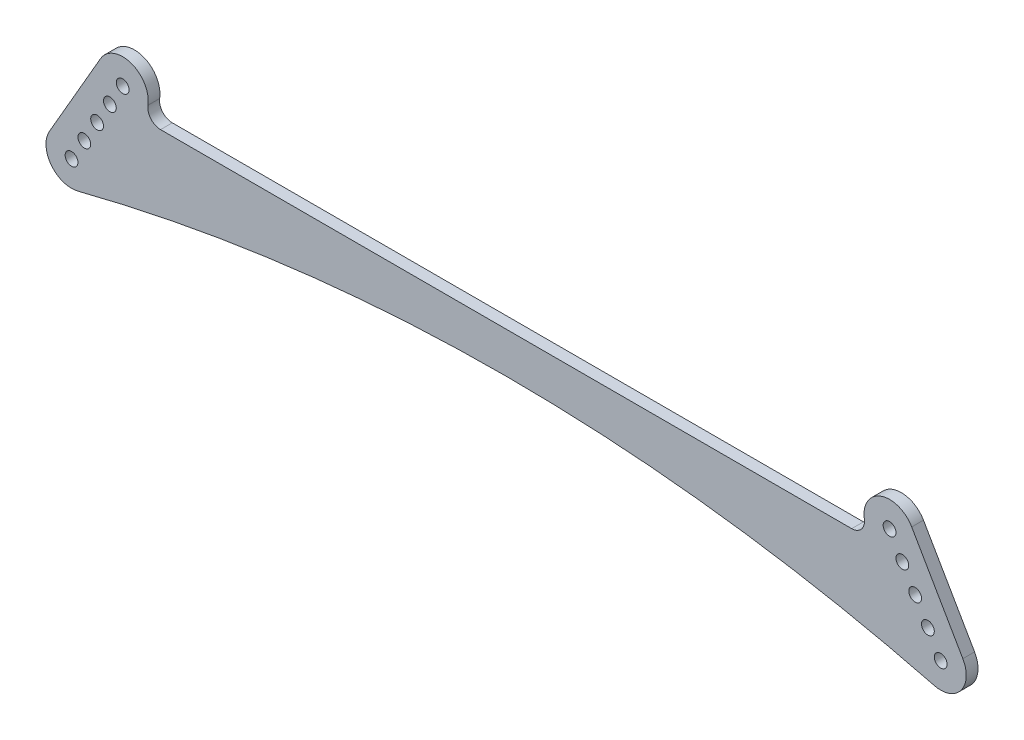
SolidWorks part; units mm, degrees
ref_plane "Front Plane" through (0, 0, 0) normal (0, 0, 1) x (1, 0, 0)
ref_plane "Top Plane" through (0, 0, 0) normal (0, 1, 0) x (1, 0, 0)
ref_plane "Right Plane" through (0, 0, 0) normal (1, 0, 0) x (0, 0, -1)
sketch "Sketch1" plane through (0, 0, 0) normal (0, 0, 1) x (1, 0, 0)
  line L0 (0, 0) -> (0, -1219.2) construction
  line L1 (0, 0) -> (-304.8, -527.9291) construction
  line L2 (0, 0) -> (304.8, -527.9291) construction
  line L3 (-104.3226, -180.692) -> (104.3226, -180.692) construction
  line L4 (-184.1757, -319.0017) -> (184.1757, -319.0017) construction
  line L5 (-190.5257, -330.0002) -> (190.5257, -330.0002) construction
  line L6 (-226.9242, -367.6443) -> (-214.2242, -345.6473)
  line L7 (214.2242, -345.6473) -> (201.5242, -323.6502)
  line L8 (226.9242, -367.6443) -> (214.2242, -345.6473)
  line L9 (-214.2242, -345.6473) -> (-201.5242, -323.6502)
  line L10 (-181.8738, -339.2973) -> (181.8738, -339.2973)
  circle A0 centre (-203.2257, -351.9973) radius 3.175
  circle A1 centre (-209.5757, -362.9958) radius 3.175
  circle A2 centre (-215.9257, -373.9943) radius 3.175
  arc A3 (-226.9242, -367.6443) -> (-212.7822, -386.2991) centre (-215.9257, -373.9943) ccw
  arc A4 (212.7822, -386.2991) -> (-212.7822, -386.2991) centre (0, -1219.2) ccw
  circle A5 centre (196.8757, -340.9987) radius 3.175
  circle A6 centre (203.2257, -351.9973) radius 3.175
  circle A7 centre (209.5757, -362.9958) radius 3.175
  circle A8 centre (215.9257, -373.9943) radius 3.175
  arc A9 (226.9242, -367.6443) -> (212.7822, -386.2991) centre (215.9257, -373.9943) cw
  circle A11 centre (-196.8757, -340.9987) radius 3.175
  circle A12 centre (-190.5257, -330.0002) radius 3.175
  arc A13 (-181.8738, -339.2973) -> (-201.5242, -323.6502) centre (-190.5257, -330.0002) ccw
  circle A14 centre (190.5257, -330.0002) radius 3.175
  arc A15 (181.8738, -339.2973) -> (201.5242, -323.6502) centre (190.5257, -330.0002) cw
  dimension "D6" = 6.35
  dimension "D8" = 25.4
  dimension "D12" = 25.4
  dimension "D1" = 30
  dimension "D2" = 609.6
  dimension "D3" = 208.6451
  dimension "D4" = 138.3097
  dimension "D5" = 12.7
  dimension "D9" = 1219.2
  dimension "D7" = 3
  dimension "D11" = 3
extrude "Boss-Extrude1" add sketch "Sketch1" along normal blind 5.842
fillet "Fillet1" radius 6.35 2 edges at (-181.8738, -339.2973, 2.921) (181.8738, -339.2973, 2.921)
sketch "Sketch2" plane through (0, 0, 5.842) normal (0, 0, 1) x (1, 0, 0)
  line L0 (-201.5242, -323.6502) -> (-179.5272, -323.6502)
  line L1 (-179.5272, -323.6502) -> (201.5242, -323.6502)
  line L2 (201.5242, -323.6502) -> (201.5242, -311.0612)
  line L3 (201.5242, -311.0612) -> (-201.5242, -311.0612)
  line L4 (-201.5242, -311.0612) -> (-201.5242, -323.6502)
  arc A0 (-177.9786, -331.9649) -> (-201.5242, -323.6502) centre (-190.5257, -330.0002) ccw construction
extrude "Cut-Extrude1" [suppressed] cut sketch "Sketch2" against normal through all
fillet "Fillet2" [suppressed] radius 3.175
